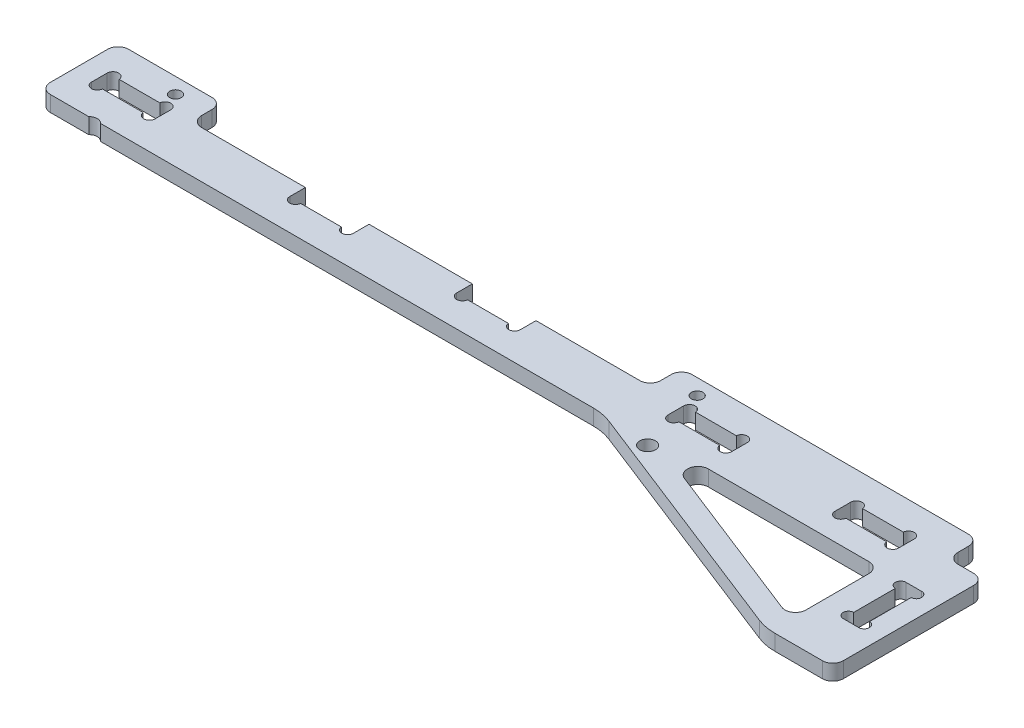
SolidWorks part; units mm, degrees
material "碳纤维"
ref_plane "前视基准面" through (0, 0, 0) normal (0, 0, 1) x (1, 0, 0)
ref_plane "上视基准面" through (0, 0, 0) normal (0, 1, 0) x (1, 0, 0)
ref_plane "右视基准面" through (0, 0, 0) normal (1, 0, 0) x (0, 0, -1)
sketch "草图1" plane through (0, 0, 0) normal (0, 1, 0) x (1, 0, 0)
  line L1 (-82.5, -4.5) -> (82.5, -4.5)
  line L2 (-82.5, -4.5) -> (-82.5, 4.5)
  line L3 (-82.5, 4.5) -> (82.5, 4.5)
  line L4 (82.5, -4.5) -> (82.5, 4.5)
  line L5 (0, 4.5) -> (0, -4.5) construction
  line L6 (-82.5, 0) -> (82.5, 0) construction
  point P0 (0, 0)
  dimension "D1" = 165
  dimension "D2" = 9
extrude "凸台-拉伸1" add sketch "草图1" along normal blind 3
sketch "草图2" plane through (0, 3, 0) normal (0, 1, 0) x (1, 0, 0)
  line L1 (-82.5, 4.5) -> (-62.5, 4.5)
  line L2 (-82.5, 4.5) -> (-82.5, 10.5)
  line L3 (-82.5, 10.5) -> (-62.5, 10.5)
  line L4 (-62.5, 4.5) -> (-62.5, 10.5)
  line L5 (-72.5, 10.5) -> (-72.5, 4.5) construction
  line L6 (-82.5, 7.5) -> (-62.5, 7.5) construction
  line L13 (82.5, -24.5) -> (82.5, -4.5)
  line L14 (-82.5, 4.5) -> (-82.5, -4.5) construction
  line L16 (82.5, 4.5) -> (25.5, 4.5)
  line L17 (-82.5, -4.5) -> (82.5, -4.5) construction
  line L21 (25.5, -4.5) -> (82.5, -4.5)
  line L22 (25.5, -4.5) -> (76.5, -24.5)
  line L23 (76.5, -24.5) -> (82.5, -24.5)
  line L24 (82.5, -4.5) -> (82.5, 4.5) construction
  line L25 (82.5, 4.5) -> (82.5, 10.5)
  line L26 (82.5, 10.5) -> (25.5, 10.5)
  line L27 (25.5, 4.5) -> (25.5, 10.5)
  line L28 (54, 10.5) -> (54, 4.5) construction
  line L29 (82.5, 7.5) -> (25.5, 7.5) construction
  point P48 (-72.5, 7.5)
  point P128 (54, 7.5)
  dimension "D1" = 108
  dimension "D2" = 20
  dimension "D3" = 6
  dimension "D4" = 6
  dimension "D5" = 20
extrude "凸台-拉伸2" add sketch "草图2" against normal blind 3
fillet "圆角1" radius 2 7 edges at (82.5, 1.5, -10.5) (25.5, 1.5, -10.5) (25.5, 1.5, -4.5) (-62.5, 1.5, -4.5) (-62.5, 1.5, -10.5) (-82.5, 1.5, 4.5) (-82.5, 1.5, -10.5)
sketch "草图3" plane through (0, 3, 0) normal (0, 1, 0) x (1, 0, 0)
  line L0 (-82.5, 3) -> (82.5, 3) construction
  line L1 (-80.5, -4.5) -> (25.5, -4.5) construction
  line L2 (82.5, -24.5) -> (82.5, 8.5) construction
  line L3 (-72.5, 10.5) -> (-72.5, 4.5) construction
  line L4 (-78.5, 1.5) -> (-66.5, 1.5)
  line L5 (-78.5, 1.5) -> (-78.5, 4.5)
  line L6 (-78.5, 4.5) -> (-66.5, 4.5)
  line L7 (-66.5, 1.5) -> (-66.5, 4.5)
  line L8 (-72.5, 4.5) -> (-72.5, 1.5) construction
  line L9 (-78.5, 3) -> (-66.5, 3) construction
  line L10 (-64.5, 10.5) -> (-80.5, 10.5) construction
  line L11 (23.5, 4.5) -> (-60.5, 4.5) construction
  line L12 (-40.5, 4.5) -> (-28.5, 4.5)
  line L13 (-40.5, 4.5) -> (-40.5, 1.5)
  line L14 (-40.5, 1.5) -> (-28.5, 1.5)
  line L15 (-28.5, 4.5) -> (-28.5, 1.5)
  line L16 (-34.5, 1.5) -> (-34.5, 4.5) construction
  line L17 (-40.5, 3) -> (-28.5, 3) construction
  line L18 (23.5, 4.5) -> (-60.5, 4.5) construction
  line L23 (3.5, 1.5) -> (-8.5, 1.5)
  line L24 (-8.5, 4.5) -> (-8.5, 1.5)
  line L25 (-82.5, 8.5) -> (-82.5, -2.5) construction
  line L26 (-62.5, 6.5) -> (-62.5, 8.5) construction
  line L27 (25.5, -4.5) -> (-62.5, -4.5) construction
  line L28 (-18.5, -4.5) -> (-18.5, 4.5) construction
  line L29 (3.5, 4.5) -> (-8.5, 4.5)
  line L30 (3.5, 4.5) -> (3.5, 1.5)
  line L31 (44, 4.5) -> (64, 4.5) construction
  line L32 (32, 1.5) -> (44, 1.5)
  line L33 (32, 1.5) -> (32, 4.5)
  line L34 (32, 4.5) -> (44, 4.5)
  line L35 (44, 1.5) -> (44, 4.5)
  line L36 (38, 4.5) -> (38, 1.5) construction
  line L37 (32, 3) -> (44, 3) construction
  line L38 (76, 1.5) -> (64, 1.5)
  line L39 (76, 1.5) -> (76, 4.5)
  line L40 (76, 4.5) -> (64, 4.5)
  line L41 (64, 1.5) -> (64, 4.5)
  line L42 (70, 4.5) -> (70, 1.5) construction
  line L43 (76, 3) -> (64, 3) construction
  line L44 (54, 4.5) -> (54, 10.5) construction
  line L45 (80.5, 10.5) -> (27.5, 10.5) construction
  line L46 (82.5, -24.5) -> (82.5, 8.5) construction
  point P6 (-72.5, 3)
  point P28 (25.5, -4.5)
  point P32 (38, 3)
  point P36 (70, 3)
  point P180 (-34.5, 3)
  dimension "D1" = 3
  dimension "D2" = 12
  dimension "D3" = 6
  dimension "D4" = 12
  dimension "D5" = 3
  dimension "D6" = 20
  dimension "D7" = 20
  dimension "D8" = 28.5
extrude "切除-拉伸1" cut sketch "草图3" against normal through all
sketch "草图5" plane through (0, 3, 0) normal (0, 1, 0) x (1, 0, 0)
  line L0 (-66.5, 4.5) -> (-78.5, 4.5) construction
  line L1 (-78.5, 3) -> (-72.5, 3) construction
  line L2 (-78.5, 4.5) -> (-78.5, 1.5) construction
  line L3 (-72.5, 3) -> (-72.5, 1.5) construction
  line L4 (-78.5, 1.5) -> (-66.5, 1.5) construction
  line L5 (-40.5, 1.5) -> (-28.5, 1.5) construction
  line L7 (-18.5, 4.5) -> (-18.5, -4.5) construction
  line L8 (-8.5, 4.5) -> (-28.5, 4.5) construction
  line L9 (-80.5, -4.5) -> (25.5, -4.5) construction
  line L10 (32, 1.5) -> (44, 1.5) construction
  line L11 (38, 4.5) -> (38, 3) construction
  line L12 (44, 4.5) -> (32, 4.5) construction
  line L13 (38, 3) -> (44, 3) construction
  line L14 (44, 1.5) -> (44, 4.5) construction
  line L15 (44, 3) -> (64, 3) construction
  line L16 (64, 4.5) -> (64, 1.5) construction
  line L17 (54, 3) -> (54, 10.5) construction
  line L18 (80.5, 10.5) -> (27.5, 10.5) construction
  circle A0 centre (-67.5, 4.5) radius 1
  circle A1 centre (-67.5, 1.5) radius 1
  circle A2 centre (-77.5, 1.5) radius 1
  circle A3 centre (-77.5, 4.5) radius 1
  circle A4 centre (-29.5, 1.5) radius 1
  circle A5 centre (-39.5, 1.5) radius 1
  circle A8 centre (2.5, 1.5) radius 1
  circle A9 centre (-7.5, 1.5) radius 1
  circle A10 centre (33, 1.5) radius 1
  circle A11 centre (43, 1.5) radius 1
  circle A12 centre (43, 4.5) radius 1
  circle A13 centre (33, 4.5) radius 1
  circle A14 centre (75, 4.5) radius 1
  circle A15 centre (65, 4.5) radius 1
  circle A16 centre (65, 1.5) radius 1
  circle A17 centre (75, 1.5) radius 1
  dimension "D1" = 2
  dimension "D2" = 2
extrude "切除-拉伸3" cut sketch "草图5" against normal through all
sketch "草图9" plane through (0, 3, 0) normal (0, 1, 0) x (1, 0, 0)
  line L1 (82.5, -24.5) -> (89.5, -24.5)
  line L2 (82.5, -24.5) -> (82.5, 4.5)
  line L3 (82.5, 4.5) -> (89.5, 4.5)
  line L4 (89.5, -24.5) -> (89.5, 4.5)
  line L5 (86, 4.5) -> (86, -24.5) construction
  line L6 (82.5, -10) -> (89.5, -10) construction
  line L7 (74, 4.5) -> (66, 4.5) construction
  line L8 (82.5, -3.5) -> (85.5, -3.5)
  line L9 (82.5, -3.5) -> (82.5, -15.5)
  line L10 (82.5, -15.5) -> (85.5, -15.5)
  line L11 (85.5, -3.5) -> (85.5, -15.5)
  line L12 (84, -15.5) -> (84, -3.5) construction
  line L13 (82.5, -9.5) -> (85.5, -9.5) construction
  point P114 (84, -9.5)
  point P180 (86, -10)
  dimension "D1" = 12
  dimension "D2" = 3
  dimension "D3" = 7
  dimension "D4" = 15
extrude "凸台-拉伸4" add sketch "草图9" against normal up to surface (3 mm away) up to face at (-12.0315, 0, -2.2039)
sketch "草图10" plane through (0, 3, 0) normal (0, 1, 0) x (1, 0, 0)
  line L1 (85.5, -3.5) -> (85.5, -15.5) construction
  line L2 (82.5, -9.5) -> (84, -9.5) construction
  line L3 (82.5, -15.5) -> (82.5, -3.5) construction
  line L4 (84, -9.5) -> (84, -15.5) construction
  line L5 (82.5, -15.5) -> (85.5, -15.5) construction
  circle A3 centre (85.5, -4.5) radius 1
  circle A4 centre (85.5, -14.5) radius 1
  circle A5 centre (82.5, -14.5) radius 1
  circle A6 centre (82.5, -4.5) radius 1
  dimension "D1" = 2
extrude "切除-拉伸5" cut sketch "草图10" against normal through all
sketch "草图6" plane through (0, 3, 0) normal (0, 1, 0) x (1, 0, 0)
  line L20 (32, 3) -> (-66.5, 3) construction
  line L21 (32, 4.5) -> (32, 1.5) construction
  line L22 (-66.5, 1.5) -> (-66.5, 4.5) construction
  line L23 (-17.25, 3) -> (-17.25, -4.5) construction
  line L24 (-78.6, 4.5) -> (-78.6, 1.5)
  line L25 (-76.4046, 1.4) -> (-68.5954, 1.4)
  line L26 (-66.4, 1.5) -> (-66.4, 4.5)
  line L27 (-68.5954, 4.6) -> (-76.4046, 4.6)
  line L28 (-78.6, 4.5) -> (-78.6, 1.5)
  line L29 (-76.4046, 1.4) -> (-68.5954, 1.4)
  line L30 (-66.4, 1.5) -> (-66.4, 4.5)
  line L31 (-68.5954, 4.6) -> (-76.4046, 4.6)
  line L32 (-80.5, -4.5) -> (25.5, -4.5) construction
  line L33 (34.0954, 4.6) -> (41.9046, 4.6)
  line L34 (31.9, 1.5) -> (31.9, 4.5)
  line L35 (41.9046, 1.4) -> (34.0954, 1.4)
  line L36 (44.1, 4.5) -> (44.1, 1.5)
  line L37 (44, 3) -> (64, 3) construction
  line L38 (44, 1.5) -> (44, 4.5) construction
  line L39 (64, 4.5) -> (64, 1.5) construction
  line L40 (54, 3) -> (54, 10.5) construction
  line L41 (80.5, 10.5) -> (27.5, 10.5) construction
  line L42 (63.9, 4.5) -> (63.9, 1.5)
  line L43 (66.0954, 1.4) -> (73.9046, 1.4)
  line L44 (76.1, 1.5) -> (76.1, 4.5)
  line L45 (73.9046, 4.6) -> (66.0954, 4.6)
  line L51 (-40.5, 4.5) -> (-66.5, 4.5) construction
  line L52 (-53.5, 4.5) -> (-53.5, -4.5) construction
  line L53 (-38.4046, 4.6) -> (-30.5954, 4.6)
  line L54 (-40.6, 1.5) -> (-40.6, 4.5)
  line L58 (82.48, -5.5198) -> (82.48, -13.4802)
  line L59 (82.5, -15.52) -> (85.5, -15.52)
  line L60 (-30.5954, 1.4) -> (-38.4046, 1.4)
  line L61 (85.52, -13.4802) -> (85.52, -5.5198)
  line L66 (-28.4, 4.5) -> (-28.4, 1.5)
  line L67 (-18.5, 4.5) -> (-18.5, -4.5) construction
  line L68 (-8.5, 4.5) -> (-28.5, 4.5) construction
  line L69 (-8.6, 4.5) -> (-8.6, 1.5)
  line L70 (-6.4046, 1.4) -> (1.4046, 1.4)
  line L71 (3.6, 1.5) -> (3.6, 4.5)
  line L72 (1.4046, 4.6) -> (-6.4046, 4.6)
  line L73 (85.5, -3.48) -> (82.5, -3.48)
  line L74 (82.48, -5.5198) -> (82.48, -13.4802)
  line L75 (82.5, -15.52) -> (85.5, -15.52)
  line L76 (85.52, -13.4802) -> (85.52, -5.5198)
  line L77 (85.5, -3.48) -> (82.5, -3.48)
  arc A16 (31.9, 4.5) -> (34.0954, 4.6) centre (33, 4.5) cw
  arc A17 (34.0954, 1.4) -> (31.9, 1.5) centre (33, 1.5) cw
  arc A18 (44.1, 1.5) -> (41.9046, 1.4) centre (43, 1.5) cw
  arc A19 (41.9046, 4.6) -> (44.1, 4.5) centre (43, 4.5) cw
  arc A20 (-76.4046, 4.6) -> (-78.6, 4.5) centre (-77.5, 4.5) ccw
  arc A21 (-78.6, 1.5) -> (-76.4046, 1.4) centre (-77.5, 1.5) ccw
  arc A22 (-68.5954, 1.4) -> (-66.4, 1.5) centre (-67.5, 1.5) ccw
  arc A23 (-66.4, 4.5) -> (-68.5954, 4.6) centre (-67.5, 4.5) ccw
  arc A24 (-76.4046, 4.6) -> (-78.6, 4.5) centre (-77.5, 4.5) ccw
  arc A25 (-78.6, 1.5) -> (-76.4046, 1.4) centre (-77.5, 1.5) ccw
  arc A26 (-68.5954, 1.4) -> (-66.4, 1.5) centre (-67.5, 1.5) ccw
  arc A27 (-66.4, 4.5) -> (-68.5954, 4.6) centre (-67.5, 4.5) ccw
  arc A28 (66.0954, 4.6) -> (63.9, 4.5) centre (65, 4.5) ccw
  arc A29 (63.9, 1.5) -> (66.0954, 1.4) centre (65, 1.5) ccw
  arc A30 (73.9046, 1.4) -> (76.1, 1.5) centre (75, 1.5) ccw
  arc A31 (76.1, 4.5) -> (73.9046, 4.6) centre (75, 4.5) ccw
  arc A36 (-40.6, 4.5) -> (-38.4046, 4.6) centre (-39.5, 4.5) cw
  arc A37 (-38.4046, 1.4) -> (-40.6, 1.5) centre (-39.5, 1.5) cw
  arc A40 (-28.4, 1.5) -> (-30.5954, 1.4) centre (-29.5, 1.5) cw
  arc A41 (-30.5954, 4.6) -> (-28.4, 4.5) centre (-29.5, 4.5) cw
  arc A42 (-6.4046, 4.6) -> (-8.6, 4.5) centre (-7.5, 4.5) ccw
  arc A43 (-8.6, 1.5) -> (-6.4046, 1.4) centre (-7.5, 1.5) ccw
  arc A44 (1.4046, 1.4) -> (3.6, 1.5) centre (2.5, 1.5) ccw
  arc A45 (3.6, 4.5) -> (1.4046, 4.6) centre (2.5, 4.5) ccw
  arc A48 (82.5, -3.48) -> (82.48, -5.5198) centre (82.5, -4.5) ccw
  arc A49 (82.48, -13.4802) -> (82.5, -15.52) centre (82.5, -14.5) ccw
  arc A50 (85.5, -15.52) -> (85.52, -13.4802) centre (85.5, -14.5) ccw
  arc A51 (85.52, -5.5198) -> (85.5, -3.48) centre (85.5, -4.5) ccw
  arc A52 (82.5, -3.48) -> (82.48, -5.5198) centre (82.5, -4.5) ccw
  arc A53 (82.48, -13.4802) -> (82.5, -15.52) centre (82.5, -14.5) ccw
  arc A54 (85.5, -15.52) -> (85.52, -13.4802) centre (85.5, -14.5) ccw
  arc A55 (85.52, -5.5198) -> (85.5, -3.48) centre (85.5, -4.5) ccw
  dimension "D1" = 0.1
  dimension "D2" = 0.02
extrude "余量" cut sketch "草图6" against normal through all
fillet "圆角2" radius 2 3 edges at (89.5, 1.5, 24.5) (89.5, 1.5, -4.5) (82.5, 1.5, -4.5)
fillet "圆角3" radius 10 2 edges at (76.5, 1.5, 24.5) (25.5, 1.5, 4.5)
sketch "草图11" plane through (0, 3, 0) normal (0, 1, 0) x (1, 0, 0)
  line L0 (34.1613, -3.6) -> (77.5, -3.6)
  line L1 (77.5, -3.6) -> (77.5, -20.5956)
  line L2 (77.5, -20.5956) -> (34.1613, -3.6)
  line L3 (27.2602, -5.1903) -> (74.7398, -23.8097) construction
  line L4 (66.0954, 1.4) -> (73.9046, 1.4) construction
  line L5 (82.5, 6.5) -> (82.5, 8.5) construction
  dimension "D1" = 5
  dimension "D2" = 5
  dimension "D3" = 4
extrude "切除-拉伸6" cut sketch "草图11" against normal through all
fillet "圆角4" radius 2 3 edges at (34.1613, 1.5, 3.6) (77.5, 1.5, 20.5956) (77.5, 1.5, 3.6)
sketch "草图12" plane through (0, 3, 0) normal (0, 1, 0) x (1, 0, 0)
  line L0 (0, 0) -> (0, -4.5) construction
  line L1 (-80.5, -4.5) -> (23.6093, -4.5) construction
  circle A0 centre (-68.5, 7.5) radius 1.1 construction
  circle A1 centre (-68.5, 7.5) radius 1.1
  circle A2 centre (31.5, 7.5) radius 1.1 construction
  circle A3 centre (31.5, 7.5) radius 1.1
  circle A4 centre (35, -5.5) radius 1.5 construction
  circle A5 centre (35, -5.5) radius 1.5
  circle A6 centre (-72, -5.5) radius 1.5 construction
  circle A7 centre (-72, -5.5) radius 1.5
extrude "切除-拉伸7" cut sketch "草图12" against normal through all
move or copy body "实体-移动/复制1" [suppressed] bodies to move or copy 117
